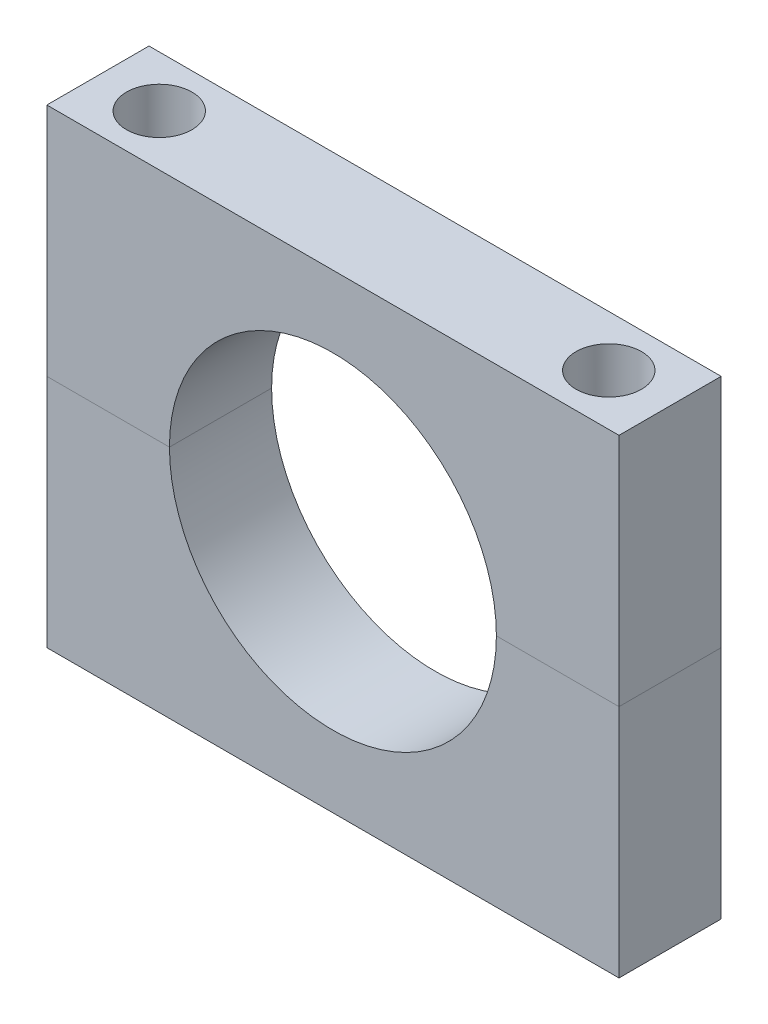
SolidWorks part; units mm, degrees
material "氧化铝"
ref_plane "前视基准面" through (0, 0, 0) normal (0, 0, 1) x (1, 0, 0)
ref_plane "上视基准面" through (0, 0, 0) normal (0, 1, 0) x (1, 0, 0)
ref_plane "右视基准面" through (0, 0, 0) normal (1, 0, 0) x (0, 0, -1)
other "Configuration Table"
sketch "草图1" plane through (0, 0, 0) normal (0, 0, 1) x (1, 0, 0)
  line L1 (-14, -11.5) -> (14, -11.5)
  line L2 (-14, -11.5) -> (-14, 11.5)
  line L3 (-14, 11.5) -> (14, 11.5)
  line L4 (14, -11.5) -> (14, 11.5)
  line L5 (-14, -11.5) -> (14, 11.5) construction
  line L6 (-14, 11.5) -> (14, -11.5) construction
  circle A0 centre (0, 0) radius 8
  point P0 (0, 0)
  dimension "D3" = 16
  dimension "D1" = 28
  dimension "D2" = 23
extrude "凸台-拉伸1" add sketch "草图1" along normal blind 5
sketch "草图2" plane through (0, 11.5, 0) normal (0, 1, 0) x (1, 0, 0)
  line L0 (-14, -2.5) -> (14, -2.5) construction
  line L1 (-14, -5) -> (-14, 0) construction
  line L2 (14, -5) -> (14, 0) construction
  line L3 (0, -5) -> (0, 0) construction
  line L4 (14, -5) -> (-14, -5) construction
  circle A0 centre (-11, -2.5) radius 1.6
  circle A1 centre (11, -2.5) radius 1.6
  dimension "D1" = 3.2
  dimension "D2" = 22
extrude "切除-拉伸1" cut sketch "草图2" against normal through all
split "分割1" trim tools "上视基准面" bodies to split 107 resulting bodies 108 109
